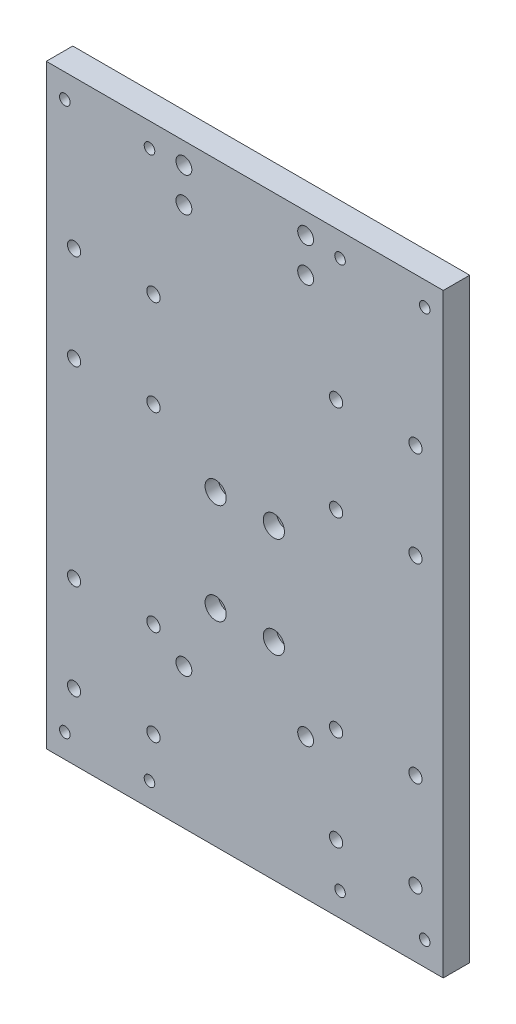
SolidWorks part; units mm, degrees
ref_plane "Alzado" through (0, 0, 0) normal (0, 0, 1) x (1, 0, 0)
ref_plane "Planta" through (0, 0, 0) normal (0, 1, 0) x (1, 0, 0)
ref_plane "Vista lateral" through (0, 0, 0) normal (1, 0, 0) x (0, 0, -1)
sketch "Croquis1" plane through (0, 0, 0) normal (0, 0, 1) x (1, 0, 0)
  line L1 (0, 0) -> (150, 0)
  line L2 (0, 0) -> (0, 225)
  line L3 (0, 225) -> (150, 225)
  line L4 (150, 0) -> (150, 225)
  dimension "D1" = 225
  dimension "D2" = 150
extrude "Saliente-Extruir1" add sketch "Croquis1" along normal blind 10
sketch "Croquis2" plane through (0, 0, 10) normal (0, 0, 1) x (1, 0, 0)
  line L0 (75, 225) -> (75, 0) construction
  line L1 (150, 225) -> (0, 225) construction
  line L2 (0, 0) -> (150, 0) construction
  line L3 (0, 195) -> (150, 195) construction
  line L4 (0, 225) -> (0, 0) construction
  line L5 (10.5, 151) -> (40.5, 151) construction
  line L6 (10.5, 169) -> (10.5, 133) construction
  line L7 (10.5, 133) -> (40.5, 133) construction
  line L8 (40.5, 133) -> (40.5, 169) construction
  line L9 (40.5, 169) -> (10.5, 169) construction
  line L10 (150, 0) -> (150, 225) construction
  line L11 (0, 97) -> (150, 97) construction
  line L12 (10.5, 61) -> (10.5, 25) construction
  line L13 (10.5, 25) -> (40.5, 25) construction
  line L14 (40.5, 25) -> (40.5, 61) construction
  line L15 (40.5, 61) -> (10.5, 61) construction
  line L16 (10.5, 43) -> (40.5, 43) construction
  circle A0 centre (10.5, 169) radius 2.5
  circle A1 centre (40.5, 169) radius 2.5
  circle A2 centre (10.5, 133) radius 2.5
  circle A3 centre (40.5, 133) radius 2.5
  circle A4 centre (109.5, 133) radius 2.5
  circle A5 centre (109.5, 169) radius 2.5
  circle A6 centre (139.5, 133) radius 2.5
  circle A7 centre (139.5, 169) radius 2.5
  circle A8 centre (139.5, 61) radius 2.5
  circle A9 centre (109.5, 61) radius 2.5
  circle A10 centre (139.5, 25) radius 2.5
  circle A11 centre (109.5, 25) radius 2.5
  circle A12 centre (40.5, 61) radius 2.5
  circle A13 centre (40.5, 25) radius 2.5
  circle A14 centre (10.5, 61) radius 2.5
  circle A15 centre (10.5, 25) radius 2.5
  dimension "D5" = 5
  dimension "D7" = 195
  dimension "D1" = 36
  dimension "D2" = 30
  dimension "D3" = 10.5
  dimension "D4" = 25
  dimension "D6" = 108
extrude "Cortar-Extruir1" cut sketch "Croquis2" against normal through all
sketch "Croquis3" plane through (0, 0, 10) normal (0, 0, 1) x (1, 0, 0)
  line L1 (150, 0) -> (150, 225) construction
  line L2 (150, 225) -> (0, 225) construction
  line L3 (0, 97) -> (150, 97) construction
  line L4 (0, 225) -> (0, 0) construction
  line L5 (64, 116) -> (64, 78) construction
  line L6 (64, 78) -> (86, 78) construction
  line L7 (86, 78) -> (86, 116) construction
  line L8 (86, 116) -> (64, 116) construction
  line L9 (75, 225) -> (75, 60) construction
  line L10 (0, 0) -> (150, 0) construction
  circle A0 centre (64, 116) radius 3
  circle A1 centre (64, 78) radius 3
  circle A2 centre (86, 78) radius 3
  circle A3 centre (86, 116) radius 3
  dimension "D7" = 6
  dimension "D2" = 97
  dimension "D3" = 19
  dimension "D4" = 19
  dimension "D5" = 11
  dimension "D6" = 11
extrude "Cortar-Extruir3" cut sketch "Croquis3" against normal through all
sketch "Croquis6" plane through (0, 0, 10) normal (0, 0, 1) x (1, 0, 0)
  line L0 (64, 116) -> (64, 78) construction
  line L1 (64, 78) -> (86, 78) construction
  line L2 (86, 78) -> (86, 116) construction
  line L3 (86, 116) -> (64, 116) construction
  circle A0 centre (64, 116) radius 4
  circle A1 centre (64, 78) radius 4
  circle A2 centre (86, 78) radius 4
  circle A3 centre (86, 116) radius 4
  dimension "D1" = 8
extrude "Cortar-Extruir5" cut sketch "Croquis6" against normal blind 5
sketch "Croquis7" plane through (0, 0, 0) normal (0, 0, -1) x (-1, 0, 0)
  line L0 (-75, 225) -> (-75, 0) construction
  line L1 (-150, 225) -> (0, 225) construction
  line L2 (0, 0) -> (-150, 0) construction
  line L3 (-150, 0) -> (-150, 225) construction
  line L4 (-150, 112.5) -> (0, 112.5) construction
  line L5 (0, 225) -> (0, 0) construction
  circle A0 centre (-143, 216) radius 2
  circle A1 centre (-111, 216) radius 2
  circle A2 centre (-39, 216) radius 2
  circle A3 centre (-7, 216) radius 2
  circle A4 centre (-7, 9) radius 2
  circle A5 centre (-39, 9) radius 2
  circle A6 centre (-111, 9) radius 2
  circle A7 centre (-143, 9) radius 2
  dimension "D1" = 4
  dimension "D2" = 32
  dimension "D3" = 7
  dimension "D4" = 9
  dimension "D5" = 9
extrude "Cortar-Extruir6" cut sketch "Croquis7" against normal through all
sketch "Croquis8" plane through (0, 0, 0) normal (0, 0, -1) x (-1, 0, 0)
  line L0 (-105, 223) -> (-105, 198) construction
  line L1 (-105, 198) -> (-45, 198) construction
  line L2 (-45, 198) -> (-45, 223) construction
  line L3 (-45, 223) -> (-105, 223) construction
  line L4 (-150, 225) -> (0, 225) construction
  line L5 (-75, 225) -> (-75, 0) construction
  line L6 (0, 0) -> (-150, 0) construction
  line L7 (-98, 217) -> (-98, 204) construction
  line L8 (-98, 204) -> (-52, 204) construction
  line L9 (-52, 204) -> (-52, 217) construction
  line L10 (-52, 217) -> (-98, 217) construction
  line L14 (-52, 53) -> (-98, 53) construction
  line L15 (-105, 63) -> (-105, 43) construction
  line L16 (-105, 43) -> (-45, 43) construction
  line L17 (-105, 63) -> (-45, 63) construction
  line L18 (-45, 63) -> (-45, 43) construction
  circle A0 centre (-98, 217) radius 3
  circle A1 centre (-52, 217) radius 3
  circle A2 centre (-98, 204) radius 3
  circle A3 centre (-52, 204) radius 3
  circle A4 centre (-98, 53) radius 3
  circle A5 centre (-52, 53) radius 3
  dimension "D13" = 6
  dimension "D2" = 30
  dimension "D3" = 2
  dimension "D4" = 30
  dimension "D5" = 60
  dimension "D6" = 23
  dimension "D7" = 23
  dimension "D8" = 46
  dimension "D9" = 13
  dimension "D10" = 6
  dimension "D11" = 6
  dimension "D12" = 25
  dimension "D14" = 10
  dimension "D15" = 10
  dimension "D16" = 20
  dimension "D17" = 135
extrude "Cortar-Extruir7" cut sketch "Croquis8" against normal through all
